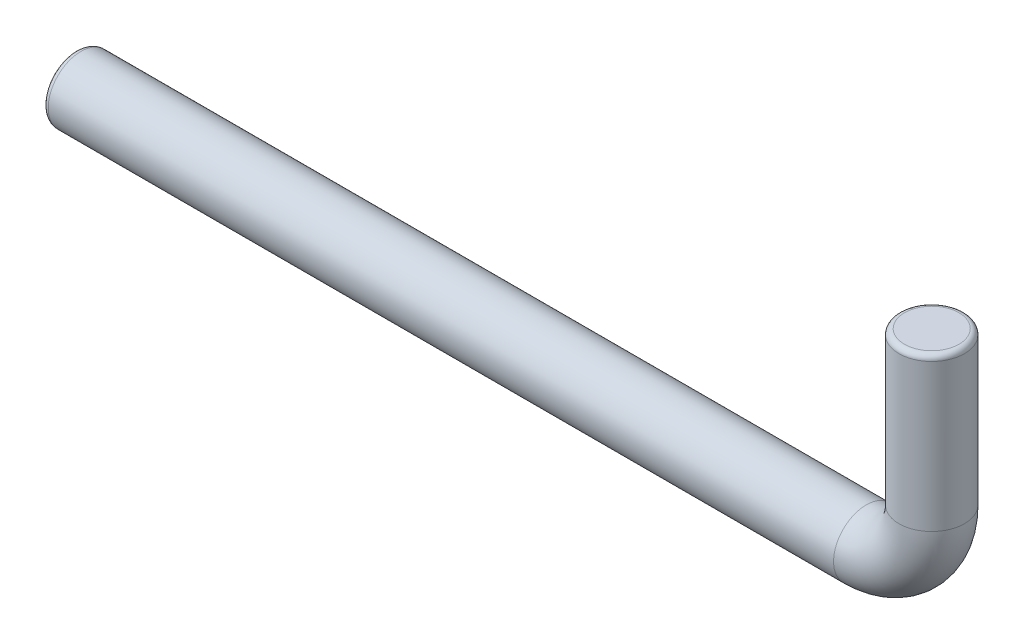
SolidWorks part; units mm, degrees
material "AISI 1020 Сталь, холоднокатаная"
ref_plane "Спереди" through (0, 0, 0) normal (0, 0, 1) x (1, 0, 0)
ref_plane "Сверху" through (0, 0, 0) normal (0, 1, 0) x (1, 0, 0)
ref_plane "Справа" through (0, 0, 0) normal (1, 0, 0) x (0, 0, -1)
sketch "Эскиз2" plane through (0, 0, 0) normal (0, 0, 1) x (1, 0, 0)
  line L0 (0, 0) -> (72.5, 0)
  line L1 (78.5, 6) -> (78.5, 20)
  arc A0 (72.5, 0) -> (78.5, 6) centre (72.5, 6) ccw
  point P6 (78.5, 0)
  dimension "D4" = 6
  dimension "D1" = 20
  dimension "D2" = 78.5
  dimension "D3" = 78.5
sketch "Эскиз4" plane through (0, 0, 0) normal (1, 0, 0) x (0, 0, -1)
  circle A0 centre (0, 0) radius 3
  dimension "D1" = 6
sweep "По траектории2" add profiles "Эскиз4" path "Эскиз2"
fillet "Скругление2" radius 0.5 2 edges at (78.5, 20, -3) (0, 0, -3)
